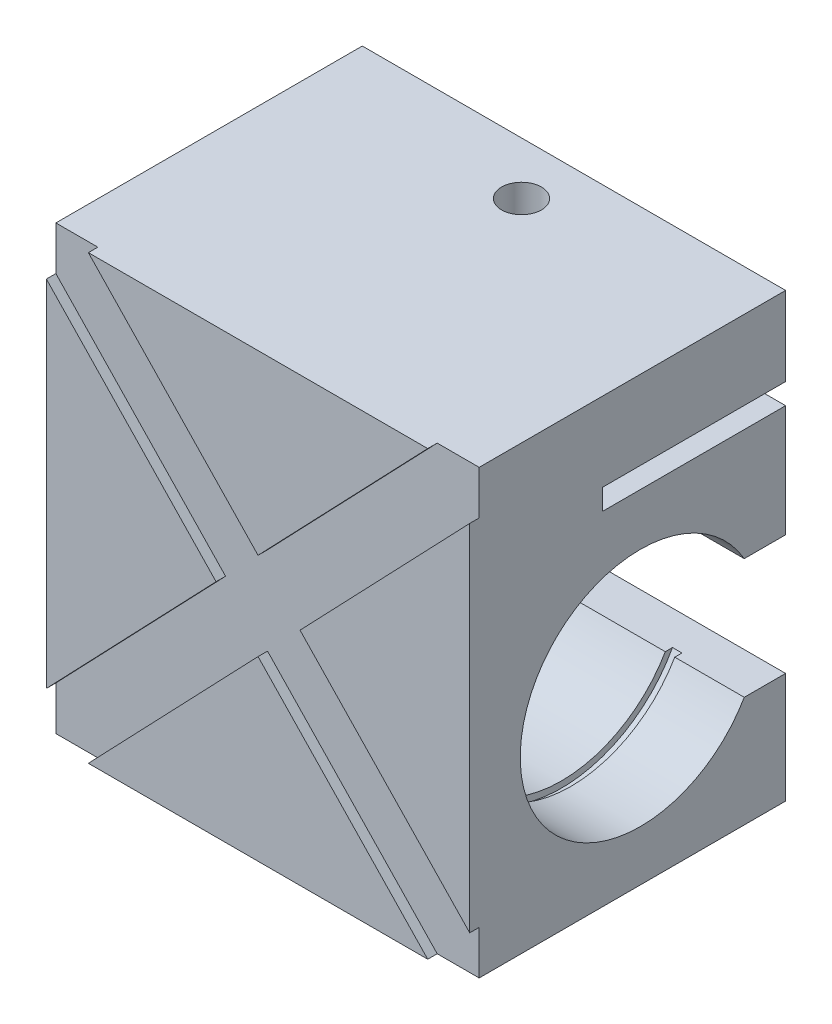
SolidWorks part; units mm, degrees
material "AISI 1020"
ref_plane "Front Plane" through (0, 0, 0) normal (0, 0, 1) x (1, 0, 0)
ref_plane "Top Plane" through (0, 0, 0) normal (0, 1, 0) x (1, 0, 0)
ref_plane "Right Plane" through (0, 0, 0) normal (1, 0, 0) x (0, 0, -1)
sketch "Sketch1" plane through (0, 0, 0) normal (0, 1, 0) x (1, 0, 0)
  line L1 (0, 0) -> (67, 0)
  line L2 (0, 0) -> (0, 50)
  line L3 (0, 50) -> (67, 50)
  line L4 (67, 0) -> (67, 50)
  dimension "D1" = 50
  dimension "D2" = 67
extrude "Boss-Extrude1" add sketch "Sketch1" along normal blind 70
sketch "Sketch2" plane through (67, 0, 0) normal (1, 0, 0) x (0, 0, -1)
  line L0 (43.4545, 36.5) -> (50, 36.5)
  line L1 (50, 70) -> (50, 0) construction
  line L2 (43.4545, 17.5) -> (50, 17.5)
  line L3 (0, 0) -> (50, 0) construction
  line L4 (0, 70) -> (0, 0) construction
  line L5 (50, 36.5) -> (60.0702, 36.5)
  line L6 (60.0702, 36.5) -> (60.0702, 17.5)
  line L7 (60.0702, 17.5) -> (50, 17.5)
  circle A0 centre (27, 27) radius 19
  line M4 (50, 0) -> (50, 70)
  dimension "D2" = 38
  dimension "D1" = 19
  dimension "D3" = 27
  dimension "D4" = 27
  dimension "D5" = 9.5
extrude "Cut-Extrude1" cut sketch "Sketch2" against normal blind 70 contours A0 | A0 L2 L0 M4 | L7 L6 L5 M4
sketch "Sketch3" plane through (67, 0, 0) normal (1, 0, 0) x (0, 0, -1)
  line L0 (50, 57.5) -> (21, 57.5)
  line L1 (50, 70) -> (50, 36.5) construction
  line L2 (21, 57.5) -> (21, 54.2)
  line L3 (21, 54.2) -> (50, 54.2)
  line L4 (0, 70) -> (50, 70) construction
  line L5 (50, 57.5) -> (56.1986, 57.5)
  line L6 (56.1986, 57.5) -> (56.1986, 54.2)
  line L7 (56.1986, 54.2) -> (50, 54.2)
  dimension "D1" = 29
  dimension "D2" = 3.3
  dimension "D3" = 12.5
extrude "Cut-Extrude2" cut sketch "Sketch3" against normal blind 70
ref_plane "Plane1" through (54.5, 0, 0) normal (1, 0, 0) x (0, 0, -1)
sketch "Sketch4" plane through (54.5, 0, 0) normal (1, 0, 0) x (0, 0, -1)
  circle A0 centre (27, 27) radius 20
  dimension "D1" = 40
extrude "Cut-Extrude3" cut sketch "Sketch4" along normal blind 1.5
ref_plane "Plane2" through (12.5, 0, 0) normal (1, 0, 0) x (0, 0, -1)
sketch "Sketch5" plane through (12.5, 0, 0) normal (1, 0, 0) x (0, 0, -1)
  circle A0 centre (27, 27) radius 20
  dimension "D1" = 40
extrude "Cut-Extrude4" cut sketch "Sketch5" against normal blind 1.5
sketch "Sketch6" plane through (0, 0, 0) normal (0, 0, 1) x (1, 0, 0)
  line L0 (0, 70) -> (67, 0) construction
  line L1 (0, 0) -> (67, 70) construction
  line L2 (0, 63.0581) -> (26.8556, 35)
  line L3 (0, 70) -> (0, 0) construction
  line L4 (0, 0) -> (67, 0) construction
  line L5 (33.5, 41.9419) -> (6.6444, 70)
  line L6 (6.6444, 0) -> (33.5, 28.0581)
  line L7 (67, 70) -> (67, 0) construction
  line L8 (-0.2909, 6.638) -> (26.8556, 35)
  line L9 (40.1444, 35) -> (67.2909, 6.638)
  line L10 (33.5, 41.9419) -> (60.3556, 70)
  line L11 (33.5, 28.0581) -> (60.3556, 0)
  line L12 (40.1444, 35) -> (67, 63.0581)
  line L13 (0, 63.0581) -> (0, 70)
  line L14 (0, 70) -> (67, 70) construction
  line L15 (60.3556, 70) -> (73.6256, 91.9525)
  line L16 (73.6256, 91.9525) -> (83.0537, 67.0726)
  line L17 (83.0537, 67.0726) -> (67, 63.0581)
  line L18 (60.3556, 0) -> (64.3196, -15.8516)
  line L19 (64.3196, -15.8516) -> (88.5535, -4.4244)
  line L20 (88.5535, -4.4244) -> (67.2909, 6.638)
  line L21 (6.6444, 0) -> (5.0094, -15.8516)
  line L22 (5.0094, -15.8516) -> (-20.1324, -10.138)
  line L23 (-20.1324, -10.138) -> (-0.2909, 6.638)
  line L24 (0, 63.0581) -> (-5.1582, 73.9973)
  line L25 (-5.1582, 73.9973) -> (7.3879, 98.1118)
  line L26 (7.3879, 98.1118) -> (6.6444, 70)
  line M10 (0, 0) -> (67, 0)
  line M11 (67, 0) -> (67, 70)
  line M12 (67, 70) -> (0, 70)
  line M13 (0, 70) -> (0, 0)
  dimension "D1" = 4.8
  dimension "D2" = 4.8
extrude "Cut-Extrude5" cut sketch "Sketch6" against normal blind 1.5 contours L9 L12 L10 L5 L2 L8 L6 L11 M11 M12 M13 M10
sketch "Sketch7" plane through (0, 70, 0) normal (0, 1, 0) x (1, 0, 0)
  line L0 (0, 50) -> (0, 1.5) construction
  line L1 (67, 50) -> (0, 50) construction
  circle A0 centre (33.5, 41.7) radius 3.15
  dimension "D3" = 6.3
  dimension "D1" = 33.5
  dimension "D2" = 8.3
extrude "Cut-Extrude6" cut sketch "Sketch7" against normal up to next
